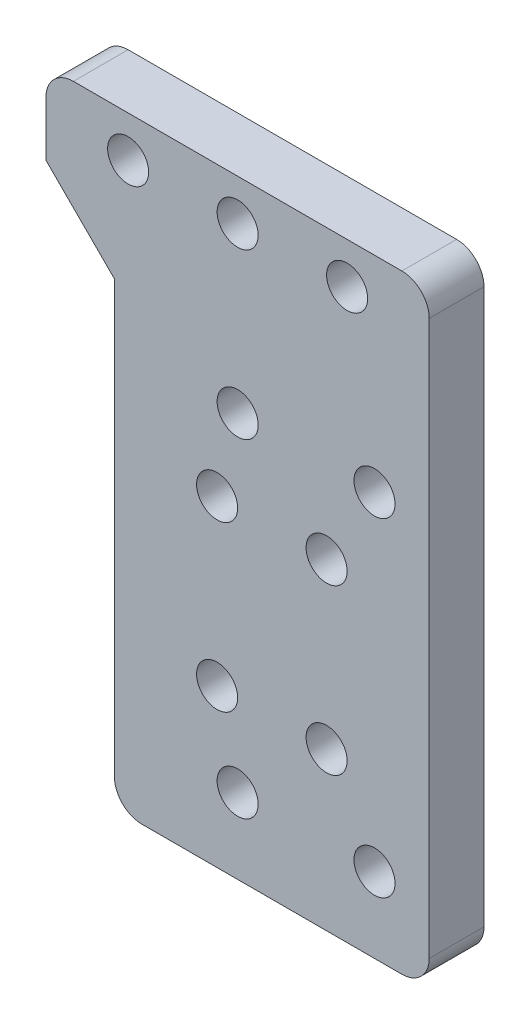
SolidWorks part; units mm, degrees
material "Thornel Mat VMA"
ref_plane "前视基准面" through (0, 0, 0) normal (0, 0, 1) x (1, 0, 0)
ref_plane "上视基准面" through (0, 0, 0) normal (0, 1, 0) x (1, 0, 0)
ref_plane "右视基准面" through (0, 0, 0) normal (1, 0, 0) x (0, 0, -1)
sketch "草图2" plane through (0, 0, 0) normal (0, 0, 1) x (1, 0, 0)
  line L0 (-14, 22.25) -> (14, 22.25)
  line L5 (14, -22.25) -> (14, 22.25)
  line L7 (-14, 16.25) -> (-9, 11.25)
  line L8 (0, -1000) -> (0, 49000) construction
  line L10 (-14, 22.25) -> (-14, 16.25)
  line L17 (-9, -22.25) -> (14, -22.25)
  line L18 (-9, 11.25) -> (-9, -22.25)
  line L19 (-14, 16.25) -> (14, 16.25) construction
  line L20 (-9, -13.75) -> (14, -13.75) construction
  line L22 (-9, 4.25) -> (14, 4.25) construction
  line L24 (-1.5, 1.25) -> (6.5, 1.25) construction
  line L25 (-1.5, 1.25) -> (-1.5, -10.75) construction
  line L26 (-1000, 0) -> (49000, 0) construction
  line L27 (13, 10.25) -> (-8, 10.25) construction
  line L28 (13, 10.25) -> (13, 4.25) construction
  line L29 (13, 4.25) -> (-8, 4.25) construction
  line L30 (-8, 10.25) -> (-8, 4.25) construction
  line L31 (2.5, -999) -> (2.5, 49001) construction
  line L32 (13, -13.75) -> (-8, -13.75) construction
  line L33 (13, -13.75) -> (13, -19.75) construction
  line L34 (13, -19.75) -> (-8, -19.75) construction
  line L35 (-8, -13.75) -> (-8, -19.75) construction
  line L36 (8, 19.25) -> (0, 19.25) construction
  circle A11 centre (0, 7.25) radius 1.5
  circle A12 centre (-1.5, 1.25) radius 1.5
  circle A13 centre (6.5, 1.25) radius 1.5
  circle A14 centre (-1.5, -10.75) radius 1.5
  circle A15 centre (6.5, -10.75) radius 1.5
  circle A16 centre (10, 7.25) radius 1.5
  circle A17 centre (0, -16.75) radius 1.5
  circle A18 centre (10, -16.75) radius 1.5
  circle A19 centre (8, 19.25) radius 1.5
  circle A21 centre (0, 19.25) radius 1.5
  circle A22 centre (-8, 19.25) radius 1.5
  point P4 (14, 0)
  point P7 (0, 22.25)
  point P41 (2.5, 1.25)
  point P47 (2.5, 10.25)
  point P48 (2.5, -13.75)
  dimension "D3" = 5
  dimension "D8" = 3
  dimension "D16" = 6
  dimension "D17" = 3
  dimension "D18" = 3
  dimension "D25" = 3
  dimension "D26" = 3
  dimension "D32" = 3
  dimension "D1" = 28
  dimension "D2" = 5
  dimension "D4" = 6
  dimension "D5" = 44.5
  dimension "D7" = 3
  dimension "D10" = 8
  dimension "D11" = 2
  dimension "D12" = 12
  dimension "D13" = 3
  dimension "D14" = 7.5
  dimension "D15" = 21
  dimension "D19" = 3
  dimension "D20" = 3
  dimension "D22" = 10
  dimension "D23" = 21
  dimension "D24" = 6
  dimension "D6" = 8.5
  dimension "D21" = 3
  dimension "D27" = 3
  dimension "D28" = 3
  dimension "D29" = 3
  dimension "D30" = 10
  dimension "D31" = 3
  dimension "D33" = 6
  dimension "D35" = 8
  dimension "D36" = 18
  dimension "D9" = 2
  dimension "D34" = 3
extrude "凸台-拉伸1" add sketch "草图2" along normal blind 4
fillet "圆角1" radius 2 4 edges at (-9, -22.25, 2) (14, -22.25, 2) (14, 22.25, 2) (-14, 22.25, 2)
